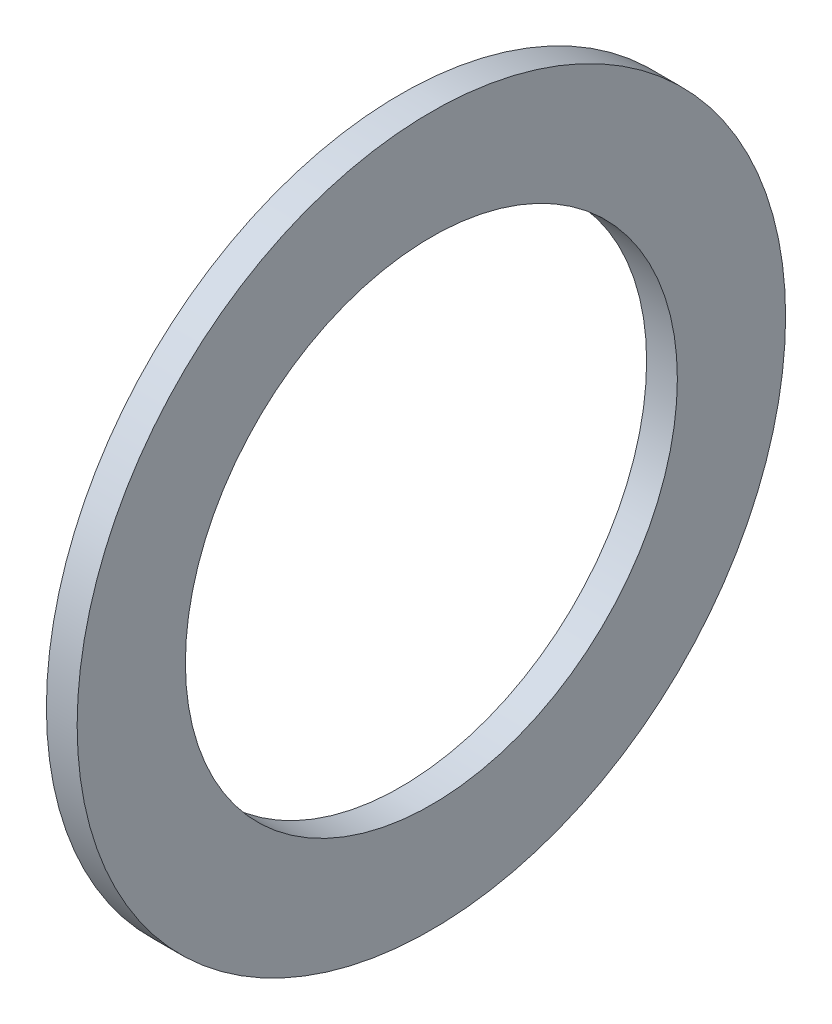
SolidWorks part; units mm, degrees
material "E-Glass Fiber"
ref_plane "Front Plane" through (0, 0, 0) normal (0, 0, 1) x (1, 0, 0)
ref_plane "Top Plane" through (0, 0, 0) normal (0, 1, 0) x (1, 0, 0)
ref_plane "Right Plane" through (0, 0, 0) normal (1, 0, 0) x (0, 0, -1)
sketch "Sketch1" plane through (0, 0, 0) normal (1, 0, 0) x (0, 0, -1)
  circle A0 centre (0, 0) radius 73.152
  circle A1 centre (0, 0) radius 50.8
  dimension "D1" = 146.304
  dimension "D2" = 101.6
extrude "Boss-Extrude1" add sketch "Sketch1" along normal blind 6.35
